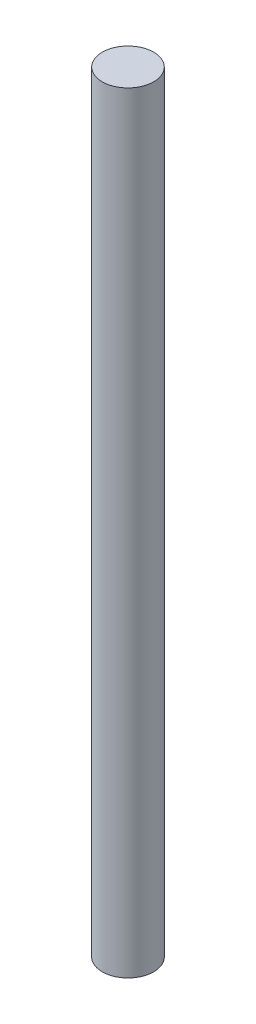
SolidWorks part; units mm, degrees
ref_plane "正面" through (0, 0, 0) normal (0, 0, 1) x (1, 0, 0)
ref_plane "平面" through (0, 0, 0) normal (0, 1, 0) x (1, 0, 0)
ref_plane "右側面" through (0, 0, 0) normal (1, 0, 0) x (0, 0, -1)
sketch "ｽｹｯﾁ1" plane through (0, 0, 0) normal (0, 1, 0) x (1, 0, 0)
  circle A0 centre (0, 0) radius 2.5
  dimension "D1" = 5
extrude "ﾎﾞｽ - 押し出し1" add sketch "ｽｹｯﾁ1" along normal mid plane 75
